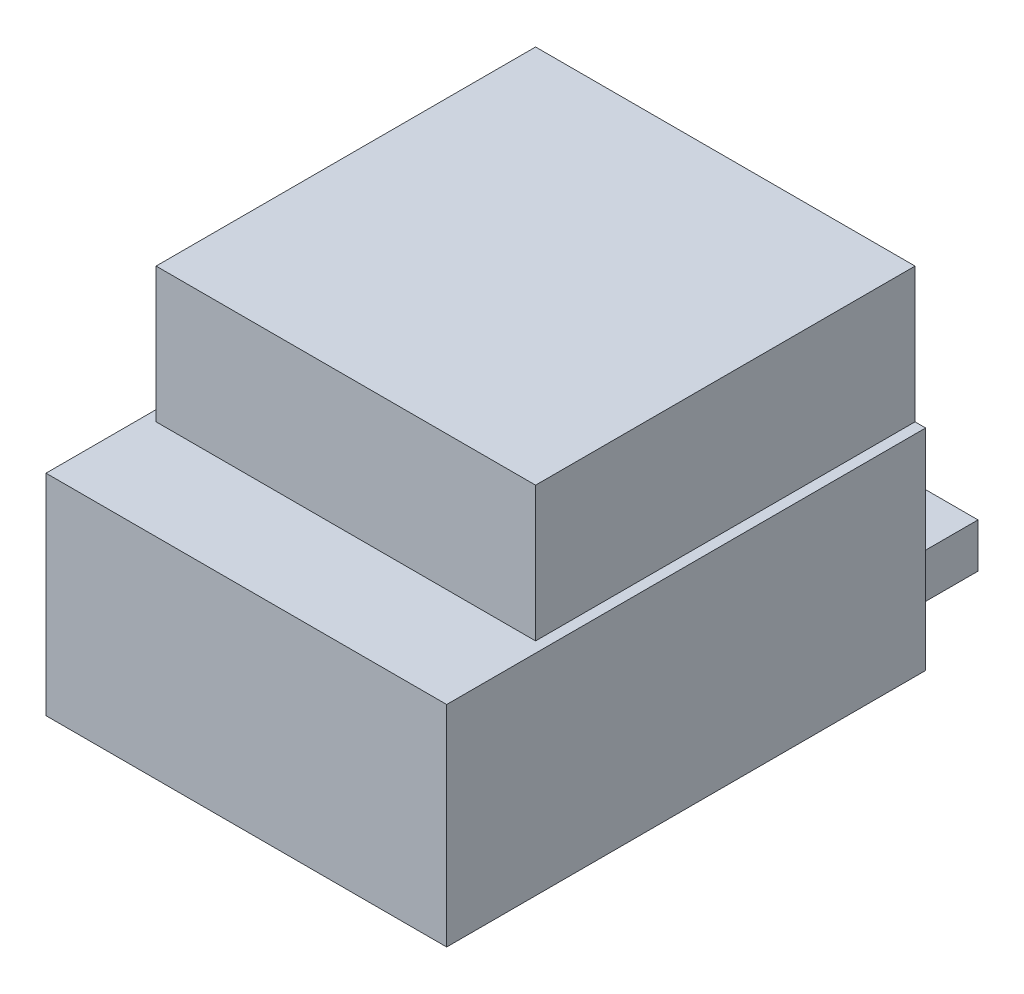
SolidWorks part; units mm, degrees
ref_plane "Piano frontale" through (0, 0, 0) normal (0, 0, 1) x (1, 0, 0)
ref_plane "Piano superiore" through (0, 0, 0) normal (0, 1, 0) x (1, 0, 0)
ref_plane "Piano destro" through (0, 0, 0) normal (1, 0, 0) x (0, 0, -1)
sketch "Schizzo1" plane through (0, 0, 0) normal (0, 1, 0) x (1, 0, 0)
  line L1 (-15.785, -18.87) -> (15.785, -18.87)
  line L2 (-15.785, -18.87) -> (-15.785, 18.87)
  line L3 (-15.785, 18.87) -> (15.785, 18.87)
  line L4 (15.785, -18.87) -> (15.785, 18.87)
  line L5 (-15.785, -18.87) -> (15.785, 18.87) construction
  line L6 (-15.785, 18.87) -> (15.785, -18.87) construction
  point P0 (0, 0)
  dimension "D1" = 31.57
  dimension "D2" = 37.74
extrude "Estrusione-Estrusione1" add sketch "Schizzo1" along normal blind 16.55
sketch "Schizzo2" plane through (0, 16.55, 0) normal (0, 1, 0) x (1, 0, 0)
  line L0 (15.785, 18.87) -> (-15.785, 18.87) construction
  line L1 (14.95, -11.03) -> (-14.95, -11.03)
  line L2 (14.95, -11.03) -> (14.95, 18.87)
  line L3 (14.95, 18.87) -> (-14.95, 18.87)
  line L4 (-14.95, -11.03) -> (-14.95, 18.87)
  line L5 (14.95, -11.03) -> (-14.95, 18.87) construction
  line L6 (14.95, 18.87) -> (-14.95, -11.03) construction
  point P0 (0, 3.92)
  point P7 (0, 18.87)
  dimension "D1" = 29.9
extrude "Estrusione-Estrusione2" add sketch "Schizzo2" along normal blind 10.63
sketch "Schizzo3" plane through (0, 0, 0) normal (0, -1, 0) x (1, 0, 0)
  line L0 (15.785, -18.87) -> (-15.785, -18.87) construction
  line L1 (13.07, -25.71) -> (-13.07, -25.71)
  line L2 (13.07, -25.71) -> (13.07, -18.87)
  line L3 (13.07, -18.87) -> (-13.07, -18.87)
  line L4 (-13.07, -25.71) -> (-13.07, -18.87)
  line L5 (13.07, -25.71) -> (-13.07, -18.87) construction
  line L6 (13.07, -18.87) -> (-13.07, -25.71) construction
  point P0 (0, -22.29)
  dimension "D1" = 26.14
  dimension "D2" = 6.84
extrude "Estrusione-Estrusione3" add sketch "Schizzo3" against normal blind 3.5 from offset 2
